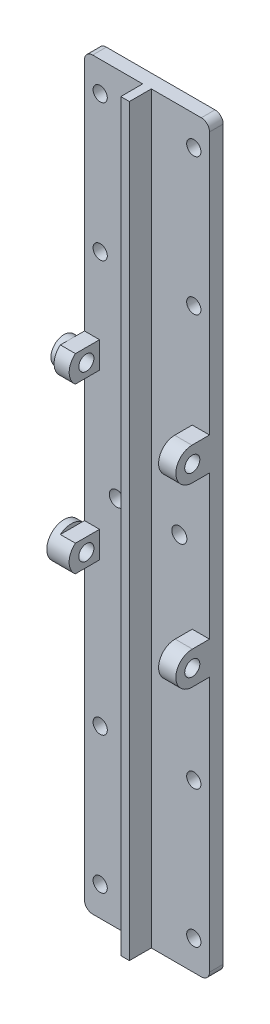
SolidWorks part; units mm, degrees
ref_plane "Front Plane" through (0, 0, 0) normal (0, 0, 1) x (1, 0, 0)
ref_plane "Top Plane" through (0, 0, 0) normal (0, 1, 0) x (1, 0, 0)
ref_plane "Right Plane" through (0, 0, 0) normal (1, 0, 0) x (0, 0, -1)
sketch "Sketch1" plane through (0, 0, 0) normal (0, 0, 1) x (1, 0, 0)
  line L1 (13.5, 160.665) -> (-11.5, 160.665)
  line L2 (13.5, 160.665) -> (13.5, -11.865)
  line L3 (13.5, -11.865) -> (-11.5, -11.865)
  line L4 (-11.5, 160.665) -> (-11.5, -11.865)
  line L5 (13.5, 160.665) -> (13.6, 160.665)
  line L6 (13.5, 160.665) -> (13.5, -11.865)
  line L7 (13.5, -11.865) -> (13.6, -11.865)
  line L8 (15.5, 158.765) -> (15.5, -9.965)
  line L9 (-11.5, -11.865) -> (-11.6, -11.865)
  line L10 (-11.5, -11.865) -> (-11.5, 160.665)
  line L11 (-11.5, 160.665) -> (-11.6, 160.665)
  line L12 (-13.5, -9.965) -> (-13.5, 158.765)
  circle A1 centre (11.85, 122.025) radius 1.65
  circle A2 centre (-9.85, 122.025) radius 1.65
  circle A3 centre (-9.85, 153.775) radius 1.65
  circle A4 centre (11.85, 153.775) radius 1.65
  circle A5 centre (11.85, 26.775) radius 1.65
  circle A6 centre (-9.85, 26.775) radius 1.65
  circle A7 centre (-9.85, -4.975) radius 1.65
  circle A8 centre (11.85, -4.975) radius 1.65
  arc A9 (-11.6, 160.665) -> (-13.5, 158.765) centre (-11.6, 158.765) ccw
  arc A10 (13.6, 160.665) -> (15.5, 158.765) centre (13.6, 158.765) cw
  arc A11 (-11.6, -11.865) -> (-13.5, -9.965) centre (-11.6, -9.965) cw
  arc A12 (13.6, -11.865) -> (15.5, -9.965) centre (13.6, -9.965) ccw
  point P0 (11.85, 20.425)
  point P1 (11.85, 7.725)
  point P3 (11.85, 14.075)
  point P5 (11.85, -4.975)
  point P7 (11.85, 26.775)
  point P9 (-9.85, 26.775)
  point P11 (-9.85, 14.075)
  point P13 (-9.85, -4.975)
  point P15 (-9.85, 7.725)
  point P17 (11.85, 153.775)
  point P19 (11.85, 122.025)
  point P21 (-9.85, 122.025)
  point P23 (-9.85, 153.775)
  point P54 (-13.5, 160.665)
  point P57 (15.5, 160.665)
  dimension "D1" = 2
  dimension "D3" = 1.9
  dimension "D2" = 2
extrude "Boss-Extrude1" add sketch "Sketch1" along normal blind 3.175 contours L6 A8 L2 A5 A1 A4 L1 L4 A3 L10 A2 A6 A7 L3 | L7 A12 L8 A10 L5 L2 L6 | A11 L9 L10 L4 L11 A9 L12
sketch "Sketch2" plane through (0, 0, 3.175) normal (0, 0, 1) x (1, 0, 0)
  line L0 (1, 160.665) -> (1, -11.865)
  line L1 (13.6, 160.665) -> (-11.6, 160.665) construction
  line L2 (13.6, -11.865) -> (-11.6, -11.865) construction
  line L3 (2, 160.665) -> (2, -11.865)
  line L4 (2, -11.865) -> (1, -11.865)
  line L5 (1, -11.865) -> (0, -11.865)
  line L6 (0, -11.865) -> (0, 160.665)
  line L7 (0, 160.665) -> (1, 160.665)
  line L8 (1, 160.665) -> (2, 160.665)
  line M3 (-11.6, -11.865) -> (13.6, -11.865)
  line M7 (13.6, 160.665) -> (-11.6, 160.665)
  dimension "D1" = 1
  dimension "D2" = 1
extrude "Boss-Extrude2" add sketch "Sketch2" along normal blind 5.08 contours L3 L0 M7 M3 | L6 L0 M3 M7
sketch "Sketch4" plane through (-13.5, 0, 0) normal (-1, 0, 0) x (0, 0, 1)
  line L0 (8.8231, 60.0768) -> (3.175, 60.0768)
  line L1 (3.175, -9.965) -> (3.175, 158.765) construction
  line L2 (3.175, 60.0768) -> (3.175, 66.2203)
  line L3 (3.175, 66.2203) -> (8.7652, 66.2203)
  line L4 (8.7993, 98.1765) -> (3.175, 98.1765)
  line L5 (3.175, 98.1765) -> (3.175, 104.2969)
  line L6 (3.175, 104.2969) -> (8.7698, 104.2969)
  circle A0 centre (6.2344, 63.1244) radius 1.75
  circle A1 centre (6.2344, 101.2244) radius 1.75
  arc A2 (8.7993, 98.1765) -> (8.7698, 104.2969) centre (6.2344, 101.2244) ccw
  arc A3 (8.8231, 60.0768) -> (8.7652, 66.2203) centre (6.2344, 63.1244) ccw
  point P0 (6.2344, 101.2244)
  point P1 (6.2344, 63.1244)
extrude "Boss-Extrude3" add sketch "Sketch4" against normal blind 3.5
sketch "Sketch5" plane through (-13.5, 0, 0) normal (-1, 0, 0) x (0, 0, 1)
  circle A0 centre (6.2344, 101.2244) radius 3.048
  circle A1 centre (6.2344, 63.1244) radius 3.9987
  circle A2 centre (6.2344, 63.1244) radius 1.75
  circle A3 centre (6.2344, 101.2244) radius 1.75
extrude "Boss-Extrude4" add sketch "Sketch5" along normal blind 1.6764
sketch "Sketch6" plane through (15.5, 0, 0) normal (-1, 0, 0) x (0, 0, 1)
  line L0 (7.1459, 56.9099) -> (3.175, 56.9099)
  line L1 (3.175, 158.765) -> (3.175, -9.965) construction
  line L2 (3.175, 56.9099) -> (3.175, 49.2901)
  line L3 (3.175, 49.2901) -> (7.2041, 49.2901)
  line L4 (7.2671, 97.9089) -> (3.175, 97.9089)
  line L5 (3.175, 97.9089) -> (3.175, 90.2911)
  line L6 (3.175, 90.2911) -> (7.0829, 90.2911)
  circle A0 centre (7.175, 53.1) radius 1.75
  circle A1 centre (7.175, 94.1) radius 1.75
  arc A2 (7.2671, 97.9089) -> (7.0829, 90.2911) centre (7.175, 94.1) cw
  arc A3 (7.1459, 56.9099) -> (7.2041, 49.2901) centre (7.175, 53.1) cw
extrude "Boss-Extrude5" add sketch "Sketch6" along normal blind 4
sketch "Sketch7" plane through (0, 0, 3.175) normal (0, 0, 1) x (1, 0, 0)
  line L0 (15.5, 90.2911) -> (15.5, 56.9099) construction
  circle A0 centre (8.5, 74.4) radius 1.75
  dimension "D2" = 3.5
  dimension "D1" = 7
extrude "Cut-Extrude1" cut sketch "Sketch7" against normal blind 4.54
sketch "Sketch8" plane through (0, 0, 3.175) normal (0, 0, 1) x (1, 0, 0)
  circle A0 centre (-6, 74.4) radius 1.75
extrude "Cut-Extrude2" cut sketch "Sketch8" against normal through all
